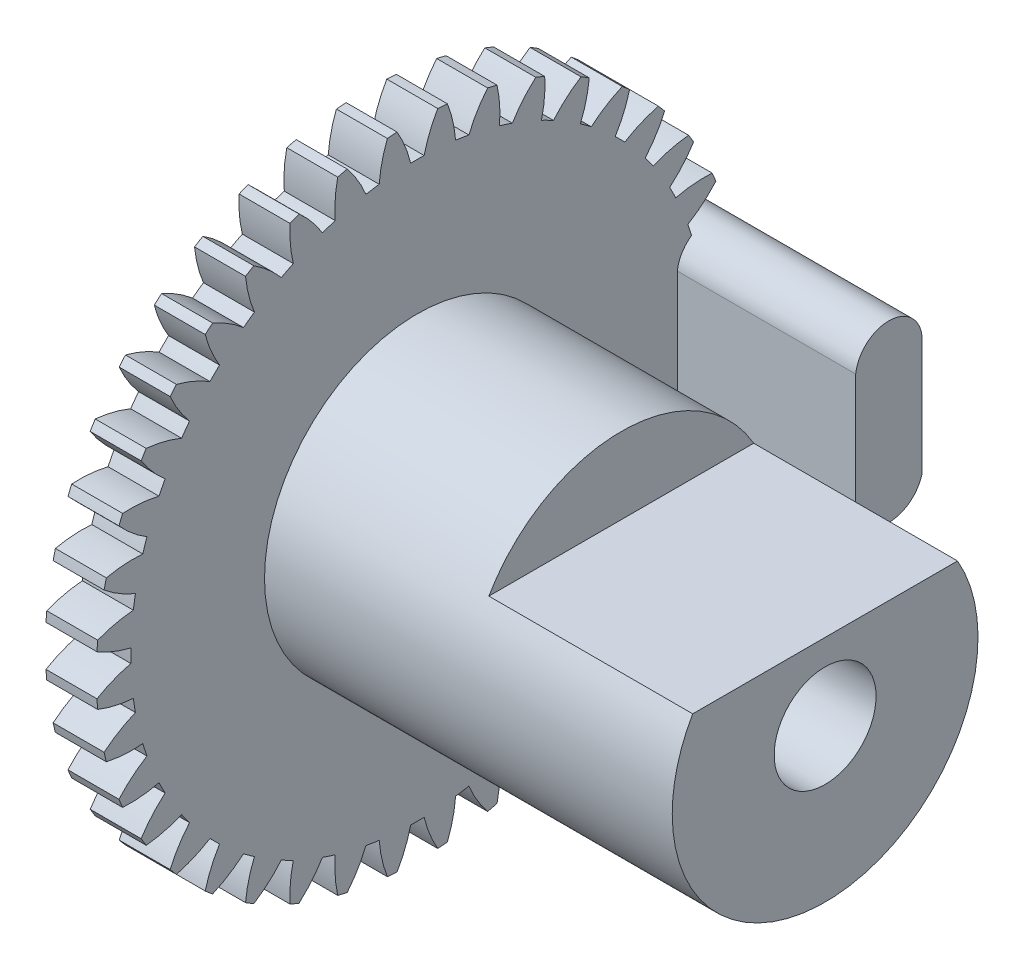
SolidWorks part; units mm, degrees
ref_plane "Plane1" through (0, 0, 0) normal (0, 0, 1) x (1, 0, 0)
ref_plane "Plane2" through (0, 0, 0) normal (0, 1, 0) x (1, 0, 0)
ref_plane "Plane3" through (0, 0, 0) normal (1, 0, 0) x (0, 0, -1)
sketch "HoldingSke" plane through (0, 0, 0) normal (0, 1, 0) x (1, 0, 0)
  line L0 (0, 0) -> (2.5535, -2.1426)
  line L1 (-15, 0) -> (100, 0) construction
  line L2 (0, 0) -> (-2.1039, 2.3779)
  line L3 (0, 0) -> (-11.863, 4.5341)
  line L4 (0, 0) -> (6.6156, 5.5511)
  line L5 (0, 0) -> (-46.8476, -17.4728)
  line L6 (0, 0) -> (-0.829, -0.5593)
  line L7 (-2.1039, 2.3779) -> (8.6586, 51.2059)
  line L8 (-76.2, 54.61) -> (-75.9, 54.61)
  line L9 (-71.009, 38.7566) -> (-53.1078, 45.2721)
  line L10 (-76.2, 71.12) -> (104.1128, 71.12)
  line L11 (0, 0) -> (-1, 0)
  line L12 (-76.2, 101.6) -> (-76.19, 101.6)
  line L13 (24.9733, 27.94) -> (52.9518, 28.4284)
  line L14 (24.9733, 27.94) -> (24.9743, 27.94)
  line L15 (24.9733, 27.94) -> (100.4006, 29.5858)
  line L16 (-63.627, -0.3) -> (-12.827, -0.3)
  circle A0 centre (0, 0) radius 1
  circle A1 centre (0, 0) radius 5.624
  circle A2 centre (0, 0) radius 37.5
  circle A3 centre (0, 0) radius 1
  dimension "MHD" = 11.248
  dimension "Hub_dia" = 75
  dimension "Bore" = 2
  dimension "MBD" = 2
  dimension "Num_teeth" = 40
  dimension "Pitch" = 3.3333
  dimension "Overall_len" = 50
  dimension "Show_teeth" = 40
  dimension "Thickness" = 1
  dimension "OAL" = 50.0001
  dimension "T_dim" = 0.3
  dimension "Ap" = 20
  dimension "H" = 19.05
  dimension "Pitch_radius" = 180.3128
  dimension "Width" = 1
  dimension "Backlash" = 0.01
  dimension "Addendum_fac" = 1
  dimension "Dedendum_fac" = 1.25
  dimension "Clearance_fac" = 0.25
  dimension "Dedendum_add" = 0.001
  dimension "Module" = 0.3
sketch "BasProSke" plane through (0, 0, 0) normal (0, 1, 0) x (1, 0, 0)
  line L0 (-10, 0) -> (60, 0) construction
  line L1 (0, 0) -> (0, 6.3)
  line L2 (0, 0) -> (1, 0)
  line L3 (1, 0) -> (1, 6.3)
  line L4 (1, 6.3) -> (0, 6.3)
  dimension "Thickness" = 1
  dimension "Diameter" = 12.6
revolve "Base-Revolve" add sketch "BasProSke" angle 360 about L0
sketch "TooCutSke" plane through (0, 0, 0) normal (1, 0, 0) x (0, 0, -1)
  line L1 (0, 0) -> (0, 107) construction
  line L2 (0, 0) -> (-0.2531, 5.9947) construction
  line L3 (0, 0) -> (-0.9409, 11.9551) construction
  line L4 (-0.2531, 5.9947) -> (-0.4704, 5.9776) construction
  arc A0 (0.1321, 5.6224) -> (-0.1321, 5.6224) centre (0, 0) ccw
  arc A1 (0.4141, 6.3118) -> (-0.4141, 6.3118) centre (0, 0) ccw
  circle A2 centre (0, 0) radius 6 construction
  circle A3 centre (0, 0) radius 5.6382 construction
  arc A4 (-0.1321, 5.6224) -> (-0.4141, 6.3118) centre (-2.4676, 5.0695) ccw
  arc A5 (0.4141, 6.3118) -> (0.1321, 5.6224) centre (2.4676, 5.0695) ccw
  dimension "Root_dia" = 11.248
  dimension "Overcut_dia" = 12.6508
  dimension "Pitch_dia" = 12
  dimension "Base_dia" = 11.2763
  dimension "Flank_rad" = 2.4
  dimension "Half_ang" = 4.5
  dimension "Half_CT" = 0.2181
extrude "ToothCut" cut sketch "TooCutSke" along normal through all
fillet "Breaks" [suppressed] radius 0.006
fillet "RootFillets" [suppressed] radius 0.076
pattern_circular "TeethCuts" count 40 every 9 about axis through (-10, 0, 0) along (1, 0, 0) of "ToothCut", "RootFillets", "Breaks"
sketch "HubNeaOneSke" plane through (0, 0, 0) normal (-1, 0, 0) x (0, 0, 1)
  circle A0 centre (0, 0) radius 5.624
  dimension "Diameter" = 11.248
extrude "HubNearOne" [suppressed] add sketch "HubNeaOneSke" along normal blind 49.0001
sketch "HubNeaBotSke" plane through (0, 0, 0) normal (-1, 0, 0) x (0, 0, 1)
  circle A0 centre (0, 0) radius 5.624
  dimension "Diameter" = 11.248
extrude "HubNearBoth" [suppressed] add sketch "HubNeaBotSke" along normal blind 24.5
ref_plane "FarPln" through (1, 0, 0) normal (1, 0, 0) x (0, 0, -1)
sketch "HubFarSke" plane through (1, 0, 0) normal (1, 0, 0) x (0, 0, -1)
  circle A0 centre (0, 0) radius 5.624
  dimension "Diameter" = 11.248
extrude "HubFar" [suppressed] add sketch "HubFarSke" along normal blind 24.5
sketch "BorSke" plane through (0, 0, 0) normal (1, 0, 0) x (0, 0, -1)
  circle A0 centre (0, 0) radius 1
  dimension "Diameter" = 2
extrude "Bore" cut sketch "BorSke" along normal mid plane 100.0001
sketch "KeySke" plane through (0, 0, 0) normal (1, 0, 0) x (0, 0, -1)
  line L0 (-0.4, 0) -> (-0.4, 1.3)
  line L1 (-0.4, 1.3) -> (0.4, 1.3)
  line L2 (0.4, 1.3) -> (0.4, 0)
  line L3 (0, 0) -> (0, 34) construction
  line L4 (-0.4, 0) -> (0.4, 0)
  dimension "Offset" = 1.3
  dimension "Width" = 0.8
extrude "Keyway" [suppressed] cut sketch "KeySke" along normal mid plane 100.0001
pattern_circular "Keyway2" [suppressed] count 2 every 90 about axis through (-10, 0, 0) along (1, 0, 0)
sketch "Schizzo1" plane through (1, 0, 0) normal (1, 0, 0) x (0, 0, -1)
  circle A0 centre (0, 0) radius 1
  circle A1 centre (0, 0) radius 3
  circle A2 centre (0, 0) radius 1 construction
  dimension "D1" = 6
extrude "Estrusione-Estrusione1" add sketch "Schizzo1" along normal blind 8
sketch "Schizzo2" plane through (9, 0, 0) normal (1, 0, 0) x (0, 0, -1)
  line L0 (-2.5981, 1.5) -> (2.5981, 1.5)
  circle A0 centre (0, 0) radius 3 construction
  arc A1 (2.5981, 1.5) -> (-2.5981, 1.5) centre (0, 0) ccw
  dimension "D1" = 1.5
extrude "Taglio-Estrusione1" cut sketch "Schizzo2" against normal blind 4
sketch "Schizzo3" plane through (1, 0, 0) normal (1, 0, 0) x (0, 0, -1)
  line L0 (5.75, 1.1) -> (5.75, -1) construction
  line L1 (6.4, 1.1752) -> (6.4, -1.1752)
  line L2 (5.1, 1.1752) -> (5.1, -1.1752)
  line L4 (5.75, 0) -> (0, 0) construction
  arc A0 (6.4, 1.1752) -> (5.1, 1.1752) centre (5.75, 1.1) ccw
  arc A1 (5.1, -1.1752) -> (6.4, -1.1752) centre (5.75, -1) ccw
  point P16 (5.1, 0)
  dimension "D1" = 2.1
  dimension "D2" = 1.3
  dimension "D3" = 5.75
  dimension "D4" = 1
  dimension "D5" = 2.3505
extrude "Estrusione-Estrusione2" add sketch "Schizzo3" along normal blind 4.5 from surface at -1 starting at face at (0, 0, -1)
equation "' \"Module@HoldingSke\" = 6.35"
equation "' \"Num_teeth@HoldingSke\" = 12"
equation "' \"Ap@HoldingSke\" =  20"
equation "' \"Ap@HoldingSke\" = 20"
equation "' \"Width@HoldingSke\" = 0.5 * 25.4"
equation "' \"Hub_dia@HoldingSke\"= 1 * 25.4"
equation "' \"Hub_dia@HoldingSke\" = 1 * 25.4"
equation "' \"Overall_len@HoldingSke\" = 1.0 * 25.4"
equation "' \"Bore@HoldingSke\" = 0.75 * 25.4"
equation "' \"T_dim@HoldingSke\" = 0.1 * 25.4"
equation "' \"Width@KeySke\" = 0.25 * 25.4"
equation "' \"Show_teeth@HoldingSke\" = 13"
equation "' \"Backlash@HoldingSke\" = 0.009 * 25.4"
equation "' \"Addendum_fac@HoldingSke\" = 1.0"
equation "' \"Dedendum_fac@HoldingSke\" = 1.25"
equation "' \"Dedendum_add@HoldingSke\" = 0.00005 * 25.4"
equation "' \"Clearance_fac@HoldingSke\" = 0.25"
equation "\"Pitch@HoldingSke\" = 1 / \"Module@HoldingSke\""
equation "\"Overcut_dia@TooCutSke\" = (\"Num_teeth@HoldingSke\" + 2 * \"Addendum_fac@HoldingSke\") / \"Pitch@HoldingSke\" + 0.002 * 25.4"
equation "\"Pitch_dia@TooCutSke\" = \"Num_teeth@HoldingSke\" / \"Pitch@HoldingSke\""
equation "\"Base_dia@TooCutSke\" = \"Num_teeth@HoldingSke\" / \"Pitch@HoldingSke\" * cos((\"Ap@HoldingSke\"  * 3.14159265 / 180))"
equation "\"Root_dia@TooCutSke\" = (\"Num_teeth@HoldingSke\" + 2) / \"Pitch@HoldingSke\" - 2 * (\"Addendum_fac@HoldingSke\" + \"Dedendum_fac@HoldingSke\") / \"Pitch@HoldingSke\" - \"Dedendum_add@HoldingSke\" * 2"
equation "\"Half_ang@TooCutSke\" = 180 / \"Num_teeth@HoldingSke\""
equation "\"Half_CT@TooCutSke\" = \"Num_teeth@HoldingSke\" / \"Pitch@HoldingSke\" * sin((3.14159265 / 2 / \"Num_teeth@HoldingSke\")) / 2 - 7 * \"Backlash@HoldingSke\" / 4"
equation "\"Flank_rad@TooCutSke\" = \"Num_teeth@HoldingSke\" / \"Pitch@HoldingSke\" / 5"
equation "\"Radius@RootFillets\" = \"Clearance_fac@HoldingSke\" / \"Pitch@HoldingSke\" + \"Dedendum_add@HoldingSke\""
equation "\"Break_rad@Breaks\" = 0.02 / \"Pitch@HoldingSke\""
equation "\"Thickness@HoldingSke\" = \"Width@HoldingSke\""
equation "\"OAL@HoldingSke\" = \"Thickness@HoldingSke\""
equation "\"MHD@HoldingSke\" = (\"Num_teeth@HoldingSke\" + 2) / \"Pitch@HoldingSke\" - 2 * (\"Addendum_fac@HoldingSke\" + \"Dedendum_fac@HoldingSke\")  / \"Pitch@HoldingSke\" - \"Dedendum_add@HoldingSke\" * 2"
equation "\"MBD@HoldingSke\" = (\"Num_teeth@HoldingSke\" + 2) / \"Pitch@HoldingSke\" - 2 * (\"Addendum_fac@HoldingSke\" + \"Dedendum_fac@HoldingSke\")  / \"Pitch@HoldingSke\" - \"Dedendum_add@HoldingSke\" * 2 - 0.002 * 25.4"
equation "\"MHD@HoldingSke\" = ((sgn( \"MHD@HoldingSke\" - \"Hub_dia@HoldingSke\" )-1)*( \"MHD@HoldingSke\" - \"Hub_dia@HoldingSke\" ))/-2+ \"Hub_dia@HoldingSke\""
equation "\"MBD@HoldingSke\" = ((sgn( \"MBD@HoldingSke\" - \"Bore@HoldingSke\" )-1)*( \"MBD@HoldingSke\" - \"Bore@HoldingSke\" ))/-2+ \"Bore@HoldingSke\""
equation "\"OAL@HoldingSke\" = ((sgn( \"OAL@HoldingSke\" - \"Overall_len@HoldingSke\" )+1)*( \"OAL@HoldingSke\" - \"Overall_len@HoldingSke\" ))/2 + \"Overall_len@HoldingSke\" + 0.000002 * 25.4"
equation "\"Num_teeth@TeethCuts\" = int( \"Show_teeth@HoldingSke\" ) + 1"
equation "\"Num_teeth@TeethCuts\" = ((sgn( \"Num_teeth@TeethCuts\" - \"Num_teeth@HoldingSke\" )-1)*( \"Num_teeth@TeethCuts\" - \"Num_teeth@HoldingSke\" ))/-2+ \"Num_teeth@HoldingSke\""
equation "\"Num_teeth@TeethCuts\" = ((sgn( \"Num_teeth@TeethCuts\" - 2.0)+1)*( \"Num_teeth@TeethCuts\" - 2.0))/2 +2.0"
equation "\"Angle@TeethCuts\" = 360.0 / \"Num_teeth@HoldingSke\""
equation "\"Diameter@BasProSke\" = (\"Num_teeth@HoldingSke\" + 2 * \"Addendum_fac@HoldingSke\") / \"Pitch@HoldingSke\""
equation "\"Thickness@BasProSke\"  = \"Thickness@HoldingSke\""
equation "' \"Fillet_rad@BasProSke\" =  \"Thickness@HoldingSke\" * 0.05"
equation "' \"Fillet_rad@BasProSke\" = \"Thickness@HoldingSke\" * 0.05"
equation "\"MHD@HoldingSke\" = ((sgn( \"MHD@HoldingSke\" - \"Root_dia@TooCutSke\" )-1)*( \"MHD@HoldingSke\" - \"Root_dia@TooCutSke\" ))/-2+ \"Root_dia@TooCutSke\""
equation "\"Diameter@HubNeaOneSke\" = \"MHD@HoldingSke\""
equation "\"Length@HubNearOne\" = \"OAL@HoldingSke\" - \"Thickness@BasProSke\""
equation "\"Diameter@HubNeaBotSke\" = \"MHD@HoldingSke\""
equation "\"Length@HubNearBoth\" = ( \"OAL@HoldingSke\" - \"Thickness@BasProSke\" ) / 2.0"
equation "\"Thickness@FarPln\" = \"Thickness@BasProSke\""
equation "\"Diameter@HubFarSke\" = \"MHD@HoldingSke\""
equation "\"Length@HubFar\" = ( \"OAL@HoldingSke\" - \"Thickness@BasProSke\" ) / 2.0"
equation "\"Diameter@BorSke\" = \"MBD@HoldingSke\""
equation "\"D1@Bore\" = \"OAL@HoldingSke\" * 2.0"
equation "\"D1@Keyway\" = \"OAL@HoldingSke\" * 2.0"
equation "\"Offset@KeySke\" = \"T_dim@HoldingSke\" + \"MBD@HoldingSke\" / 2.0"
